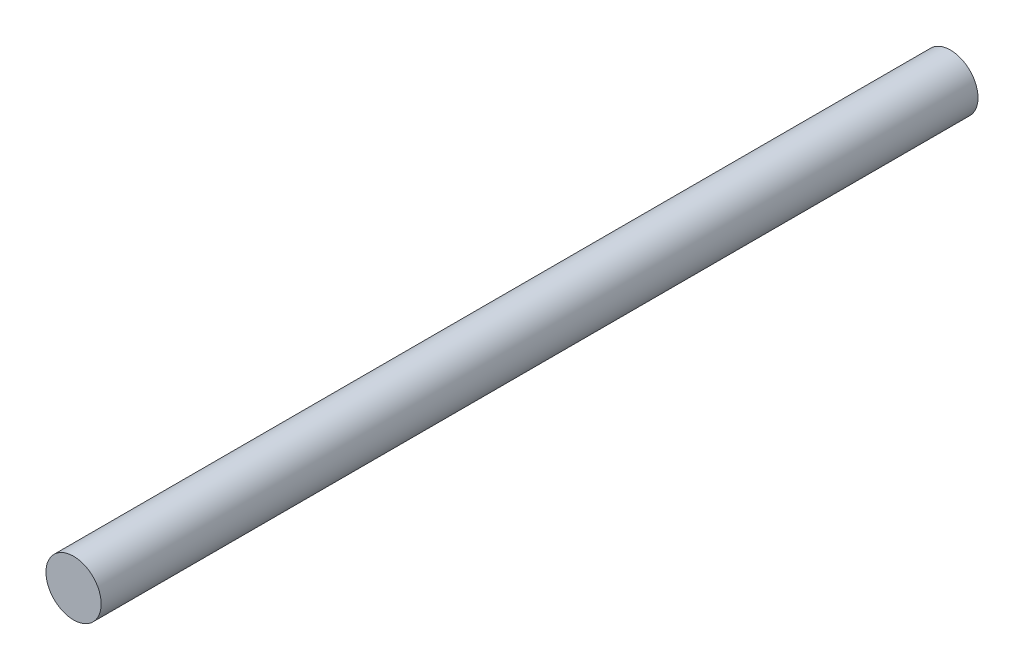
SolidWorks part; units mm, degrees
ref_plane "Front Plane" through (0, 0, 0) normal (0, 0, 1) x (1, 0, 0)
ref_plane "Top Plane" through (0, 0, 0) normal (0, 1, 0) x (1, 0, 0)
ref_plane "Right Plane" through (0, 0, 0) normal (1, 0, 0) x (0, 0, -1)
sketch "Sketch1" plane through (0, 0, 0) normal (0, 0, 1) x (1, 0, 0)
  circle A0 centre (0, 0) radius 2
  dimension "D1" = 4
extrude "Boss-Extrude1" add sketch "Sketch1" along normal mid plane 63.5
